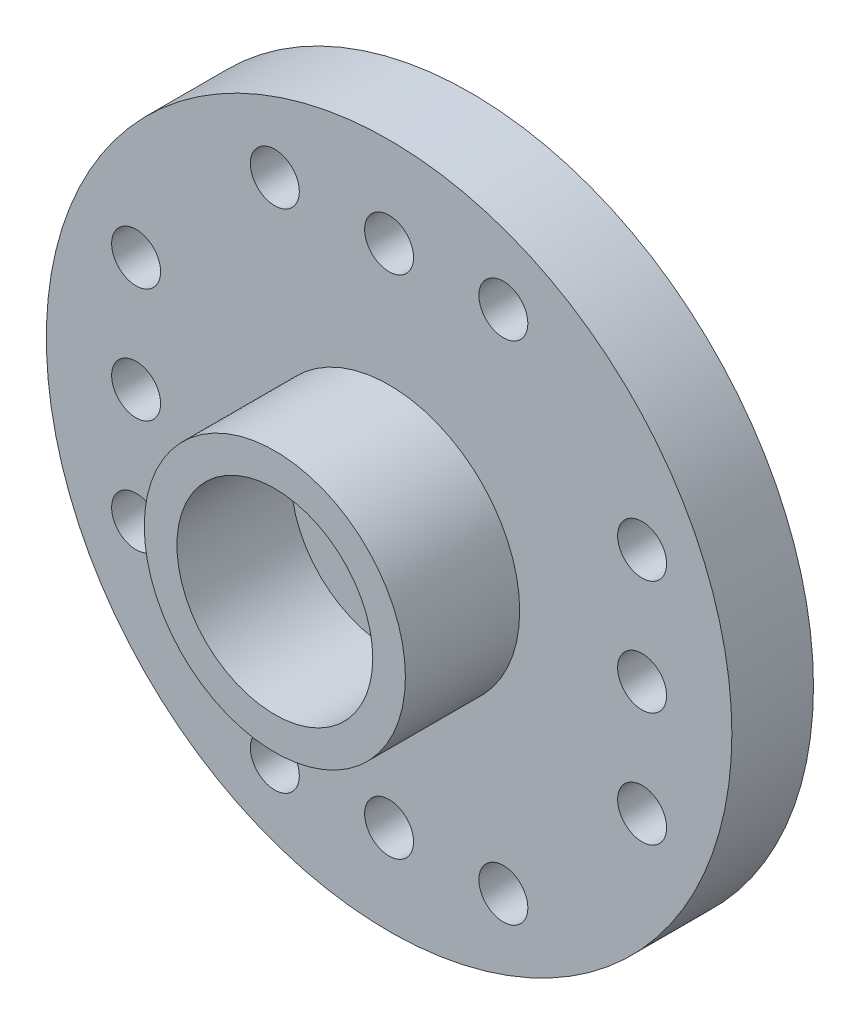
SolidWorks part; units mm, degrees
ref_plane "Alzado" through (0, 0, 0) normal (0, 0, 1) x (1, 0, 0)
ref_plane "Planta" through (0, 0, 0) normal (0, 1, 0) x (1, 0, 0)
ref_plane "Vista lateral" through (0, 0, 0) normal (1, 0, 0) x (0, 0, -1)
sketch "Croquis1" plane through (0, 0, 0) normal (0, 0, 1) x (1, 0, 0)
  circle A0 centre (0, 0) radius 10.5
  circle A1 centre (0, 0) radius 1.5
  dimension "D1" = 21
  dimension "D2" = 3
extrude "Saliente-Extruir1" add sketch "Croquis1" along normal blind 2.5
sketch "Croquis2" plane through (0, 0, 2.5) normal (0, 0, 1) x (1, 0, 0)
  circle A0 centre (0, 0) radius 4
  circle A1 centre (0, 0) radius 3
  dimension "D1" = 8
  dimension "D2" = 6
extrude "Saliente-Extruir2" add sketch "Croquis2" along normal blind 3.5
sketch "Croquis3" plane through (0, 0, 2.5) normal (0, 0, 1) x (1, 0, 0)
  line L0 (-7.75, -3.1186) -> (-7.75, 4.0097) construction
  line L1 (0, 0) -> (-18.6693, 0) construction
  circle A0 centre (0, 0) radius 7.75 construction
  circle A1 centre (-7.75, 0) radius 0.75
  circle A2 centre (-7.75, 3.5) radius 0.75
  circle A3 centre (-7.75, -3.5) radius 0.75
  circle A4 centre (3.5, 7.75) radius 0.75
  circle A5 centre (0, 7.75) radius 0.75
  circle A6 centre (-3.5, 7.75) radius 0.75
  circle A7 centre (7.75, -3.5) radius 0.75
  circle A8 centre (7.75, 0) radius 0.75
  circle A9 centre (7.75, 3.5) radius 0.75
  circle A10 centre (-3.5, -7.75) radius 0.75
  circle A11 centre (0, -7.75) radius 0.75
  circle A12 centre (3.5, -7.75) radius 0.75
  point P33 (0, 0)
  dimension "D1" = 15.5
  dimension "D2" = 1.5
  dimension "D5" = 1.5
  dimension "D6" = 1.5
  dimension "D3" = 3.5
  dimension "D4" = 3.5
  dimension "D7" = 4
extrude "Cortar-Extruir1" cut sketch "Croquis3" against normal blind 3.5
